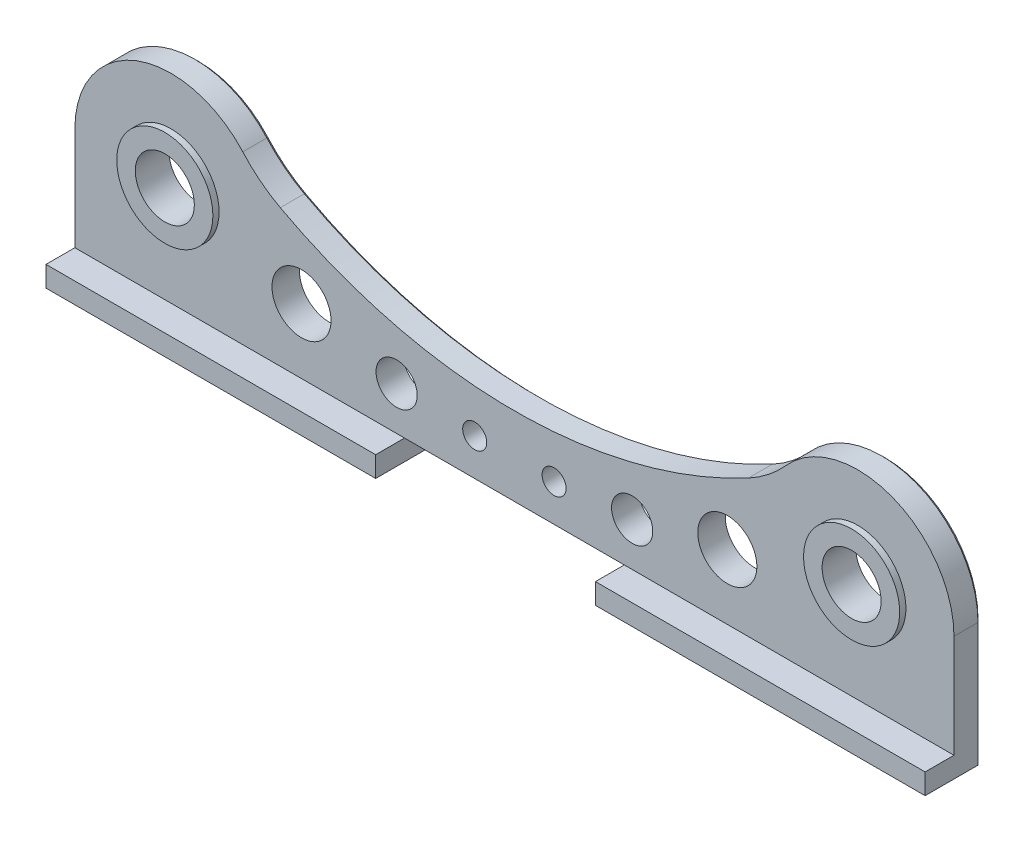
SolidWorks part; units mm, degrees
ref_plane "Front Plane" through (0, 0, 0) normal (0, 0, 1) x (1, 0, 0)
ref_plane "Top Plane" through (0, 0, 0) normal (0, 1, 0) x (1, 0, 0)
ref_plane "Right Plane" through (0, 0, 0) normal (1, 0, 0) x (0, 0, -1)
sketch "Sketch3" plane through (0, 0, 0) normal (0, 0, 1) x (1, 0, 0)
  line L0 (-64, -73.6274) -> (-64, -91.6274)
  line L1 (-64, -91.6274) -> (0, -91.6274)
  line L3 (0, -91.6274) -> (0, -77.2013)
  arc A2 (-38.0579, -66.3209) -> (-64, -73.6274) centre (-50, -73.6274) ccw
  arc A5 (-38.0579, -66.3209) -> (0, -77.2013) centre (0, -5.2013) ccw
  dimension "D1" = 64
  dimension "D2" = 28
  dimension "D4" = 50
  dimension "D6" = 18
  dimension "D7" = 72
extrude "Boss-Extrude1" add sketch "Sketch3" along normal blind 4 separate body contours A5 L3 L1 L0 A2
sketch "Sketch6" plane through (0, 0, 4) normal (0, 0, 1) x (1, 0, 0)
  circle A0 centre (-50, -73.6274) radius 7
  dimension "D1" = 14
extrude "Boss-Extrude2" add sketch "Sketch6" along normal blind 0.9
sketch "Sketch7" plane through (0, 0, 4.9) normal (0, 0, 1) x (1, 0, 0)
  circle A0 centre (-50, -73.6274) radius 4.3
  dimension "D1" = 8.6
extrude "Cut-Extrude1" cut sketch "Sketch7" against normal blind 20 contours A0
fillet "Fillet1" radius 20 1 edges at (-38.0579, -66.3209, 2)
sketch "Sketch8" plane through (0, 0, 4) normal (0, 0, 1) x (1, 0, 0)
  line L1 (-64, -91.6274) -> (0, -91.6274)
  line L2 (-64, -91.6274) -> (-64, -88.6274)
  line L3 (-64, -88.6274) -> (0, -88.6274)
  line L4 (0, -91.6274) -> (0, -88.6274)
  dimension "D1" = 3
extrude "Boss-Extrude3" add sketch "Sketch8" along normal blind 4.2
sketch "Sketch10" plane through (0, 0, 8.2) normal (0, 0, 1) x (1, 0, 0)
  line L0 (-16, -88.6274) -> (-16, -91.6274)
  line L1 (0, -88.6274) -> (-64, -88.6274) construction
  line L2 (-64, -91.6274) -> (0, -91.6274) construction
  line L3 (-16, -91.6274) -> (0, -91.6274)
  line L4 (0, -91.6274) -> (0, -88.6274)
  line L5 (0, -88.6274) -> (-16, -88.6274)
  line L6 (-64, -91.6274) -> (0, -91.6274) construction
  dimension "D1" = 16
extrude "Cut-Extrude2" cut sketch "Sketch10" against normal blind 20
sketch "Sketch11" plane through (0, 0, 4) normal (0, 0, 1) x (1, 0, 0)
  circle A0 centre (-50, -73.6274) radius 11 construction
  circle A1 centre (-31, -79.1861) radius 4.3
  circle A3 centre (-31, -79.1861) radius 8 construction
  circle A4 centre (-17.148, -82.3304) radius 3
  circle A5 centre (-5.7798, -83.2333) radius 1.75
  dimension "D1" = 22
  dimension "D2" = 31
  dimension "D3" = 8.6
  dimension "D4" = 6
  dimension "D5" = 3.5
extrude "Cut-Extrude3" cut sketch "Sketch11" against normal blind 20
mirror "Mirror1" about plane through (0, -91.6274, 4) normal (-1, 0, 0) of bodies 108
chamfer "Chamfer1" distance 0.5 angle 45 12 edges at (-54.9843, -60.5448, 0) (0, -77.2013, 0) (-37.0073, -66.7055, 0) (0, -88.6274, 0) (-16, -90.1274, 0) (-40, -91.6274, 0) (-64, -82.6274, 0) (54.9843, -60.5448, 0) (64, -82.6274, 0) (40, -91.6274, 0) (37.0073, -66.7055, 0) (16, -90.1274, 0)
